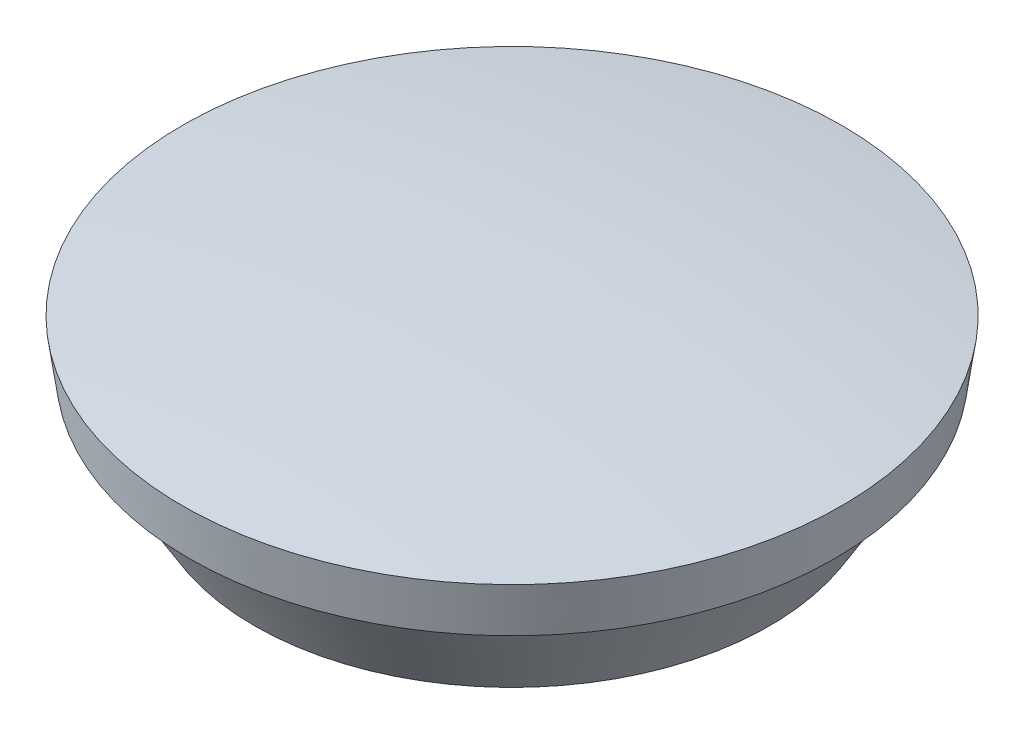
SolidWorks part; units mm, degrees
material "Silicon Rubber"
ref_plane "Front Plane" through (0, 0, 0) normal (0, 0, 1) x (1, 0, 0)
ref_plane "Top Plane" through (0, 0, 0) normal (0, 1, 0) x (1, 0, 0)
ref_plane "Right Plane" through (0, 0, 0) normal (1, 0, 0) x (0, 0, -1)
sketch "Sketch1" plane through (0, 0, 0) normal (1, 0, 0) x (0, 0, -1)
  line L0 (26.0878, 274.978) -> (26.0878, 232.1195)
  line L2 (40.135, 299.274) -> (-40.135, 299.274) construction
  line L5 (0, 324) -> (3.2968, 324)
  line L8 (0, 324) -> (0, 0) construction
  line L9 (26.0878, 262.3641) -> (26.0878, 259.4973) construction
  line L12 (40.135, 302.9291) -> (40.135, 295.6188)
  line L16 (0, 0) -> (51.9362, 327.9125) construction
  line L17 (0, 324) -> (0, 332) construction
  line L18 (26.0878, 274.978) -> (26.0878, 268.978) construction
  line L19 (26.0878, 268.978) -> (26.0878, 248.978) construction
  line L20 (26.0878, 268.978) -> (42.6019, 268.978) construction
  line L21 (26.0878, 274.978) -> (43.5522, 274.978) construction
  line L22 (26.0878, 248.978) -> (39.4342, 248.978) construction
  line L23 (0, 0) -> (-51.9362, 327.9125) construction
  line L24 (-47.4003, 299.274) -> (-47.4003, 268.978) construction
  line L25 (-47.4003, 268.978) -> (-42.6019, 268.978) construction
  line L26 (0, 332) -> (0, 76.96) construction
  line L27 (0, 76.96) -> (400, 76.96) construction
  line L28 (0, 76.96) -> (-400, 76.96) construction
  line L29 (-200, 76.96) -> (-200, 184.46) construction
  line L30 (200, 76.96) -> (200, 184.46) construction
  line L31 (-200, 184.46) -> (-200, 182.57) construction
  line L32 (-200, 182.57) -> (400, 182.57) construction
  line L33 (-200, 182.57) -> (-400, 182.57) construction
  line L38 (0, 186.1152) -> (0, 324)
  line L39 (26.0878, 232.1195) -> (26.0878, 182.57) construction
  line L41 (21.6442, 226.0993) -> (26.0878, 226.0993)
  line L42 (26.0878, 226.0993) -> (26.0878, 186.1152)
  line L43 (26.0878, 186.1152) -> (0, 186.1152)
  line L44 (0, 0) -> (575.122, 0) construction
  arc A0 (-298.7691, 144.7791) -> (305.6579, 129.6043) centre (0, 0) cw construction
  spline S0 degree 3 poles (21.6442, 226.0993) (21.9584, 226.1509) (22.4049, 226.153) (22.896, 226.3321) (23.44, 226.7494) (24.2443, 227.2014) (25.0066, 227.9724) (25.5796, 228.9522) (25.8622, 230.393) (26.0228, 231.4436) (26.0878, 232.1195) knots 0 0 0 0 0.091924 0.112491 0.205673 0.333714 0.459267 0.602423 0.748839 1 1 1 1
  spline S1 degree 3 poles (3.2968, 324) (4.1972, 323.8396) (5.699, 323.816) (7.6935, 323.4297) (9.2722, 323.1563) (10.7507, 322.8538) (12.1816, 322.5577) (13.6372, 322.313) (14.8643, 321.9117) (15.9115, 321.5662) (16.81, 321.2491) (17.7339, 321.0149) (18.8379, 320.6416) (19.931, 320.1935) (21.0686, 319.6948) (22.141, 319.2627) (23.2156, 318.6856) (24.4371, 318.1163) (25.6762, 317.3518) (27.1066, 316.7518) (28.4318, 315.7832) (29.7322, 314.8939) (31.058, 313.93) (32.1959, 312.8581) (33.3378, 311.8503) (34.4539, 310.9646) (35.3895, 309.8867) (36.5078, 309.0949) (37.2942, 308.0208) (38.1233, 307.1238) (38.9048, 306.0961) (39.4724, 304.6349) (40.2774, 303.734) (40.135, 302.9291) knots 0 0 0 0 0.061585 0.100795 0.136831 0.1697 0.202569 0.235438 0.269088 0.289473 0.309858 0.333319 0.353706 0.388423 0.412965 0.437514 0.46634 0.495168 0.528354 0.564387 0.59925 0.638593 0.670824 0.709635 0.743897 0.773612 0.805519 0.839783 0.864953 0.89467 0.922395 0.951224 1 1 1 1
  spline S2 degree 3 poles (40.135, 295.6188) (39.9636, 294.7131) (39.7869, 293.3689) (39.1095, 291.6901) (38.6019, 290.4599) (37.8418, 289.2392) (36.9195, 288.2279) (35.9232, 287.2651) (34.974, 286.2515) (33.8311, 285.3463) (32.8233, 284.2966) (31.8701, 283.2868) (30.7668, 282.4387) (29.8742, 281.4644) (28.8604, 280.5152) (28.0567, 279.5119) (27.1438, 278.5569) (26.4968, 277.0287) (26.0081, 275.8567) (26.0878, 274.978) knots 0 0 0 0 0.108356 0.15601 0.210945 0.263562 0.322855 0.370186 0.4254 0.484692 0.539909 0.595126 0.646549 0.701764 0.749093 0.808384 0.85195 0.901837 1 1 1 1
  point P10 (0, 299.274)
  point P63 (0, 299.274)
  dimension "D3" = 9
  dimension "D1" = 40.135
  dimension "D2" = 324
  dimension "D4" = 8
  dimension "D5" = 3.2968
  dimension "D6" = 4.4435
  dimension "D7" = 6.0202
  dimension "D8" = 7.7403
  dimension "D9" = 6
  dimension "D10" = 20
  dimension "D11" = 9.317
  dimension "D12" = 10.7504
  dimension "D13" = 255.04
  dimension "D14" = 107.5
  dimension "D15" = 107.5
  dimension "D16" = 332
  dimension "D17" = 105.61
  dimension "D18" = 105.61
  dimension "D19" = 12.1838
  dimension "D20" = 13.6172
  dimension "D21" = 15.0506
  dimension "D22" = 15.9106
  dimension "D23" = 16.7707
  dimension "D24" = 17.7739
  dimension "D25" = 18.6341
  dimension "D26" = 20.0676
  dimension "D27" = 21.0708
  dimension "D28" = 22.0743
  dimension "D29" = 23.2209
  dimension "D30" = 24.3677
  dimension "D31" = 25.6578
  dimension "D32" = 27.0911
  dimension "D33" = 28.3811
  dimension "D34" = 29.8146
  dimension "D35" = 30.9613
  dimension "D36" = 32.2513
  dimension "D37" = 33.3981
  dimension "D38" = 34.4014
  dimension "D39" = 35.4048
  dimension "D40" = 36.5516
  dimension "D41" = 37.2681
  dimension "D42" = 38.1282
  dimension "D43" = 38.8449
  dimension "D44" = 39.4183
  dimension "D45" = 39.9917
  dimension "D46" = 323.8567
  dimension "D47" = 323.7133
  dimension "D48" = 323.4267
  dimension "D49" = 323.1399
  dimension "D50" = 322.8533
  dimension "D51" = 322.5666
  dimension "D52" = 322.2799
  dimension "D53" = 321.8499
  dimension "D54" = 321.5632
  dimension "D55" = 321.2765
  dimension "D56" = 320.9899
  dimension "D57" = 320.7031
  dimension "D58" = 320.1297
  dimension "D59" = 319.6998
  dimension "D60" = 319.2698
  dimension "D61" = 318.6965
  dimension "D62" = 318.1231
  dimension "D63" = 317.4064
  dimension "D64" = 316.6897
  dimension "D65" = 315.8296
  dimension "D66" = 314.8263
  dimension "D67" = 313.9663
  dimension "D68" = 312.8195
  dimension "D69" = 311.8162
  dimension "D70" = 310.9562
  dimension "D71" = 309.9528
  dimension "D72" = 308.9493
  dimension "D73" = 308.0893
  dimension "D74" = 307.086
  dimension "D75" = 306.0826
  dimension "D76" = 304.9359
  dimension "D77" = 303.9325
  dimension "D78" = 302.9291
sketch "Sketch2" plane through (0, 0, 0) normal (1, 0, 0) x (0, 0, -1)
  line L0 (0, 324) -> (3.2968, 324) construction
  line L1 (26.5078, 274.997) -> (26.5078, 273.8486)
  line L2 (40.5477, 295.5407) -> (40.5477, 314.2386)
  line L3 (40.135, 295.6188) -> (40.135, 302.9302) construction
  line L4 (40.135, 295.6188) -> (26.0878, 274.978) construction
  line L5 (0, 324.42) -> (3.4084, 324.42) construction
  line L6 (3.2968, 324) -> (40.135, 302.9302) construction
  line L7 (3.4084, 324.42) -> (40.555, 303.1738) construction
  line L8 (26.0878, 274.978) -> (26.0878, 232.1195) construction
  line L9 (40.555, 295.4895) -> (26.435, 274.7417) construction
  line L10 (0, 5) -> (0, 407.9498) construction
  line L12 (26.5078, 273.8486) -> (38.5078, 273.8486) construction
  line L13 (26.5078, 274.997) -> (26.5078, 232.1195) construction
  line L14 (38.5078, 273.8486) -> (45.76, 323.5611) construction
  line L17 (40.5477, 314.2386) -> (45.93, 323.5611) construction
  line L18 (45.93, 323.5611) -> (45.76, 323.5611) construction
  line L19 (0, 186.1152) -> (0, 324) construction
  line L20 (0, 324) -> (0, 332) construction
  line L21 (40.555, 295.4895) -> (40.555, 303.1738) construction
  line L22 (0, 5) -> (47.1644, 328.2999) construction
  line L23 (45.93, 323.5611) -> (46.473, 323.5611) construction
  line L24 (46.473, 323.5611) -> (39.2208, 273.8486) construction
  line L25 (39.2208, 273.8486) -> (26.5078, 273.8486)
  line L26 (44.7753, 321.5611) -> (46.1813, 321.5611)
  line L27 (44.7753, 321.5611) -> (40.5477, 314.2386)
  line L28 (46.1813, 321.5611) -> (39.2208, 273.8486)
  spline S0 degree 1 poles (40.5477, 295.5407) (26.5078, 274.997) knots 0 0 1 1 construction
  spline S1 degree 3 poles (40.135, 295.6188) (39.9636, 294.7131) (39.7869, 293.3689) (39.1095, 291.6901) (38.6019, 290.4599) (37.8418, 289.2392) (36.9195, 288.2279) (35.9232, 287.2651) (34.974, 286.2515) (33.8311, 285.3463) (32.8233, 284.2966) (31.8701, 283.2868) (30.7668, 282.4387) (29.8742, 281.4644) (28.8604, 280.5152) (28.0567, 279.5119) (27.1438, 278.5569) (26.4968, 277.0287) (26.0081, 275.8567) (26.0878, 274.978) knots 0 0 0 0 0.108356 0.15601 0.210945 0.263562 0.322855 0.370186 0.4254 0.484692 0.539909 0.595126 0.646549 0.701764 0.749093 0.808384 0.85195 0.901837 1 1 1 1 construction
  spline S2 degree 3 poles (40.5477, 295.5407) (40.4477, 295.0127) (40.2928, 293.9708) (39.9309, 292.5875) (39.5162, 291.5815) (39.1084, 290.578) (38.4397, 289.317) (37.3314, 288.0326) (36.3684, 287.1154) (35.6302, 286.3401) (35.0165, 285.7627) (34.3943, 285.2472) (33.6355, 284.5566) (32.9204, 283.7714) (32.1297, 282.9861) (31.4852, 282.4595) (30.915, 281.9635) (30.3717, 281.3913) (29.7828, 280.8046) (29.2276, 280.2622) (28.7248, 279.6749) (28.1804, 279.0397) (27.6518, 278.4702) (27.3081, 277.8768) (26.9952, 277.1272) (26.598, 276.1645) (26.4648, 275.4705) (26.5078, 274.997) knots 0 0 0 0 0.062544 0.125088 0.15636 0.187632 0.250176 0.31272 0.375264 0.406536 0.437808 0.46908 0.500352 0.562896 0.594168 0.62544 0.656713 0.687985 0.719257 0.750529 0.781801 0.813073 0.844345 0.875617 0.906889 0.938161 1.000705 1.000705 1.000705 1.000705
  point P38 (0, 328)
  dimension "D4" = 1.1484
  dimension "D5" = 8.3
  dimension "D6" = 30
  dimension "D7" = 45.93
  dimension "D8" = 40.39
  dimension "D9" = 8.3
  dimension "D10" = 40.5477
  dimension "D3" = 12
  dimension "D11" = 18.6979
  dimension "D12" = 2
  dimension "D13" = 5
  dimension "D1" = 0.42
  dimension "D2" = 0.42
revolve "Revolve6" [suppressed] add sketch "Sketch2" angle 360 about L10
sketch "Sketch3" [suppressed] plane through (0, 0, 0) normal (1, 0, 0) x (0, 0, -1)
  line L0 (44.1979, 321.5611) -> (40.5477, 314.2386) construction
  line L3 (46.1813, 321.5611) -> (-46.1813, 321.5611) construction
  line L4 (44.7753, 321.5611) -> (-44.7753, 321.5611) construction
  line L5 (40.5477, 314.2386) -> (-40.5477, 314.2386) construction
  line L6 (40.5477, 314.2386) -> (54.812, 333.8718)
  line L8 (54.812, 333.8718) -> (54.812, 347.837)
  line L9 (54.812, 347.837) -> (0, 347.837)
  line L10 (0, 347.837) -> (0, 311.6751)
  line L11 (0, 186.1152) -> (0, 324) construction
  line L12 (0, 311.6751) -> (40.5477, 311.6751)
  line L13 (40.5477, 311.6751) -> (40.5477, 314.2386)
  dimension "D1" = 36
  dimension "D2" = 54.812
revolve "Cut-Revolve1" [suppressed] cut sketch "Sketch3" angle 360 about L10
sketch "Sketch4" [suppressed] plane through (0, 273.8486, 0) normal (0, -1, 0) x (1, 0, 0)
  line L0 (0, 0) -> (36, 0) construction
  line L1 (0, 0) -> (-31.1769, 18) construction
  circle A0 centre (0, 0) radius 36 construction
  circle A1 centre (-31.1769, 18) radius 3
  circle A2 centre (36, 0) radius 3
  dimension "D1" = 72
  dimension "D3" = 6
  dimension "D4" = 6
  dimension "D2" = 150
extrude "Boss-Extrude1" [suppressed] add sketch "Sketch4" along normal blind 2
sketch "Sketch5" [suppressed] plane through (0, 263.8486, 0) normal (0, -1, 0) x (1, 0, 0)
  circle A0 centre (36, 0) radius 3.175
  circle A1 centre (-31.1769, 18) radius 3.175
  dimension "D1" = 6.35
  dimension "D2" = 6.35
extrude "Boss-Extrude2" [suppressed] add sketch "Sketch5" along normal blind 5
chamfer "Chamfer2" [suppressed] distance 9 angle 4
sketch "Sketch7" plane through (0, 0, 0) normal (1, 0, 0) x (0, 0, -1)
  line L0 (0, 5) -> (0, 407.9498) construction
  line L1 (26.5078, 273.8486) -> (39.2208, 273.8486) construction
  line L2 (39.2208, 273.8486) -> (39.2208, 272.3194)
  line L4 (26.5078, 273.8486) -> (26.5078, 274.3486)
  line L5 (26.5078, 274.3486) -> (39.2208, 274.3486)
  line L6 (39.2208, 274.3486) -> (39.2208, 273.8486)
  circle A0 centre (0, -0.122) radius 275.25 construction
  arc A1 (39.2208, 272.3194) -> (26.5078, 273.8486) centre (0, -0.122) ccw
  dimension "D1" = 550.5
  dimension "D2" = 0.5
revolve "Revolve7" [suppressed] add sketch "Sketch7" angle 360 about L10
sketch "Sketch9" [suppressed] plane through (0, 271.8486, 0) normal (0, -1, 0) x (1, 0, 0)
  circle A0 centre (36, 0) radius 1.5
  circle A1 centre (-31.1769, 18) radius 1.5
  dimension "D1" = 3
  dimension "D2" = 3
extrude "Cut-Extrude1" [suppressed] cut sketch "Sketch9" against normal blind 6
sketch "Sketch10" [suppressed] plane through (0, 271.8486, 0) normal (0, -1, 0) x (1, 0, 0)
  circle A0 centre (36, 0) radius 2
  circle A1 centre (-31.1769, 18) radius 2
  dimension "D1" = 4
  dimension "D2" = 4
extrude "Cut-Extrude2" [suppressed] cut sketch "Sketch10" against normal blind 0.5
chamfer "Chamfer3" [suppressed] distance 0.55 angle 45
sketch "Sketch11" plane through (0, 0, 0) normal (1, 0, 0) x (0, 0, -1)
  line L0 (46.1813, 321.5611) -> (44.7753, 321.5611)
  line L1 (44.7753, 321.5611) -> (36.8783, 308.577)
  line L2 (46.1813, 321.5611) -> (47.1962, 328.6282)
  line L3 (0, 332) -> (0, 324)
  arc A0 (305.6579, 129.6043) -> (-298.7691, 144.7791) centre (0, 0) ccw construction
  arc A1 (47.1962, 328.6282) -> (0, 332) centre (0, 0) ccw
  arc A2 (36.8783, 308.577) -> (0, 324) centre (0.7725, 274.0456) ccw
  spline S0 degree 3 poles (3.2968, 324) (4.1972, 323.8396) (5.699, 323.816) (7.6935, 323.4297) (9.2722, 323.1563) (10.7507, 322.8538) (12.1816, 322.5577) (13.6372, 322.313) (14.8643, 321.9117) (15.9115, 321.5662) (16.81, 321.2491) (17.7339, 321.0149) (18.8379, 320.6416) (19.931, 320.1935) (21.0686, 319.6948) (22.141, 319.2627) (23.2156, 318.6856) (24.4371, 318.1163) (25.6762, 317.3518) (27.1066, 316.7518) (28.4318, 315.7832) (29.7322, 314.8939) (31.058, 313.93) (32.1959, 312.8581) (33.3378, 311.8503) (34.4539, 310.9646) (35.3895, 309.8867) (36.5078, 309.0949) (37.2942, 308.0208) (38.1233, 307.1238) (38.9048, 306.0961) (39.4724, 304.6349) (40.2774, 303.734) (40.135, 302.9291) knots 0 0 0 0 0.061585 0.100795 0.136831 0.1697 0.202569 0.235438 0.269088 0.289473 0.309858 0.333319 0.353706 0.388423 0.412965 0.437514 0.46634 0.495168 0.528354 0.564387 0.59925 0.638593 0.670824 0.709635 0.743897 0.773612 0.805519 0.839783 0.864953 0.89467 0.922395 0.951224 1 1 1 1 construction
  dimension "D1" = 332
  dimension "D2" = 49.9604
  dimension "D3" = 98.173
revolve "Revolve8" add sketch "Sketch11" angle 360 about L10
